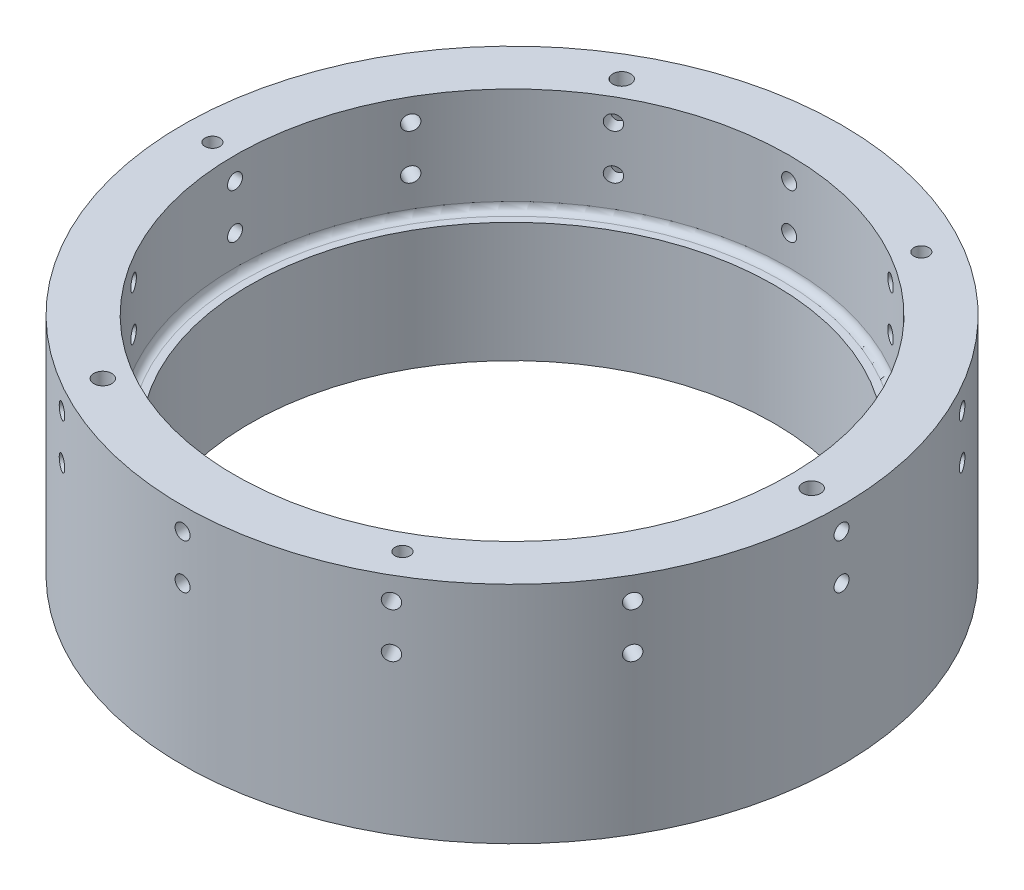
SolidWorks part; units mm, degrees
material "延性铁"
ref_plane "前视基准面" through (0, 0, 0) normal (0, 0, 1) x (1, 0, 0)
ref_plane "上视基准面" through (0, 0, 0) normal (0, 1, 0) x (1, 0, 0)
ref_plane "右视基准面" through (0, 0, 0) normal (1, 0, 0) x (0, 0, -1)
sketch "草图1" plane through (0, 0, 0) normal (1, 0, 0) x (0, 0, -1)
  line L0 (0, 0) -> (0, 159.2157) construction
  line L1 (-110, 75) -> (-110, 0)
  line L2 (-110, 0) -> (-87.5, 0)
  line L3 (-87.5, 0) -> (-87.5, 40)
  line L4 (-87.5, 40) -> (-92.5, 40)
  line L5 (-92.5, 40) -> (-92.5, 75)
  line L6 (-92.5, 75) -> (-110, 75)
  dimension "D1" = 175
  dimension "D2" = 185
  dimension "D3" = 75
  dimension "D4" = 40
  dimension "D5" = 220
revolve "旋转1" add sketch "草图1" angle 360 about L0
sketch "草图2" plane through (0, 75, 0) normal (0, 1, 0) x (1, 0, 0)
  circle A0 centre (100, 0) radius 3
  dimension "D2" = 6
  dimension "D4" = 100
extrude "切除-拉伸1" cut sketch "草图2" against normal through all
hole_wizard "M6 螺纹孔1" positions "草图3" profile "草图4" tap size "M6" standard "GB"
sketch "草图3" plane through (0, 75, 0) normal (0, 1, 0) x (1, 0, 0)
  line L0 (-100, 0) -> (0, 0) construction
  line L1 (0, 0) -> (100, 0) construction
  point P0 (-100, 0)
sketch "草图4" plane through (-100, 75, 0) normal (1, 0, 0) x (0, 0, 1)
  line L0 (0, 0) -> (0, 16.5022)
  line L1 (0, 16.5022) -> (2.5, 15)
  line L2 (2.5, 15) -> (2.5, 0)
  line L5 (2.5, 0) -> (0, 0)
  line L10 (0, 16.5022) -> (-2.5, 15) construction
  line L11 (0, -6.35) -> (0, 107.95) construction
  dimension "螺纹孔钻头直径" = 5
  dimension "螺纹孔钻头深度" = 15
  dimension "导头角度" = 118
cosmetic thread "孔螺蚊线2" parameters "D1"=12, "D2"=6
hole_wizard "M6 螺纹孔2" positions "草图5" profile "草图6" tap size "M6" standard "GB"
sketch "草图5" plane through (0, 0, 0) normal (0, -1, 0) x (-1, 0, 0)
  point P0 (100, 0)
sketch "草图6" plane through (-100, 0, 0) normal (1, 0, 0) x (0, 0, -1)
  line L0 (0, 0) -> (0, 16.5022)
  line L1 (0, 16.5022) -> (2.5, 15)
  line L2 (2.5, 15) -> (2.5, 0)
  line L5 (2.5, 0) -> (0, 0)
  line L10 (0, 16.5022) -> (-2.5, 15) construction
  line L11 (0, -6.35) -> (0, 107.95) construction
  dimension "螺纹孔钻头直径" = 5
  dimension "螺纹孔钻头深度" = 15
  dimension "导头角度" = 118
cosmetic thread "孔螺蚊线3" parameters "D1"=12, "D2"=6
hole_wizard "M6 螺纹孔3" positions "草图7" profile "草图8" tap size "M6" standard "GB"
sketch "草图7" plane through (0, 0, 0) normal (0, 0, 1) x (1, 0, 0)
  line L0 (92.5, 75) -> (-92.5, 75) construction
  line L1 (110, 75) -> (-110, 75) construction
  point P0 (0, 67.5)
  point P6 (0, 52.5)
  dimension "D1" = 7.5
  dimension "D2" = 22.5
sketch "草图8" plane through (0, 67.5, 0) normal (1, 0, 0) x (0, 1, 0)
  line L0 (0, 0) -> (0, 110)
  line L1 (0, 110) -> (2.5, 110)
  line L2 (2.5, 110) -> (2.5, 0)
  line L5 (2.5, 0) -> (0, 0)
  line L11 (0, -6.35) -> (0, 107.95) construction
  dimension "通孔螺纹孔钻头直径" = 5
  dimension "通孔螺纹孔钻头深度" = 110
cosmetic thread "孔螺蚊线4" parameters "D2"=6
cosmetic thread "孔螺蚊线5" parameters "D2"=6
sketch "草图9" plane through (0, 75, 0) normal (0, 1, 0) x (1, 0, 0)
  circle A0 centre (-100, 0) radius 2.5
  dimension "D1" = 5
extrude "切除-拉伸2" cut sketch "草图9" against normal through all
pattern_circular "阵列(圆周)1" count 3 over 360 about axis through (0, 0, 0) along (0, 1, 0) of "切除-拉伸1", "M6 螺纹孔2", "M6 螺纹孔1", "切除-拉伸2"
fillet "圆角1" radius 2.5 1 edges at (0, 40, -92.5)
pattern_circular "阵列(圆周)2" count 12 over 360 about axis through (0, 0, 0) along (0, -1, 0) of "M6 螺纹孔3"
